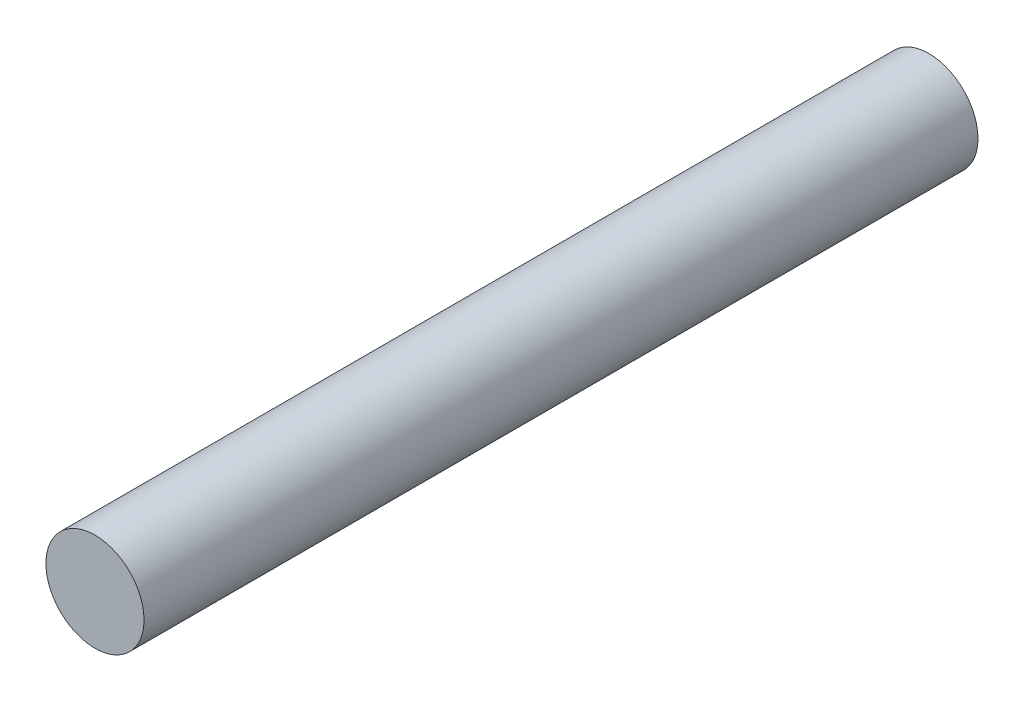
SolidWorks part; units mm, degrees
material "6061 Alloy"
ref_plane "Front Plane" through (0, 0, 0) normal (0, 0, 1) x (1, 0, 0)
ref_plane "Top Plane" through (0, 0, 0) normal (0, 1, 0) x (1, 0, 0)
ref_plane "Right Plane" through (0, 0, 0) normal (1, 0, 0) x (0, 0, -1)
other "Length"
sketch "Sketch1" plane through (0, 0, 0) normal (0, 0, 1) x (1, 0, 0)
  circle A0 centre (0, 0) radius 4
  dimension "D1" = 8
extrude "Boss-Extrude1" add sketch "Sketch1" along normal mid plane 68
equation "\"Diameter\"= \"Diameter\""
equation "\"D1@Sketch1\"= \"Diameter\""
equation "\"Length\"= 2000"
